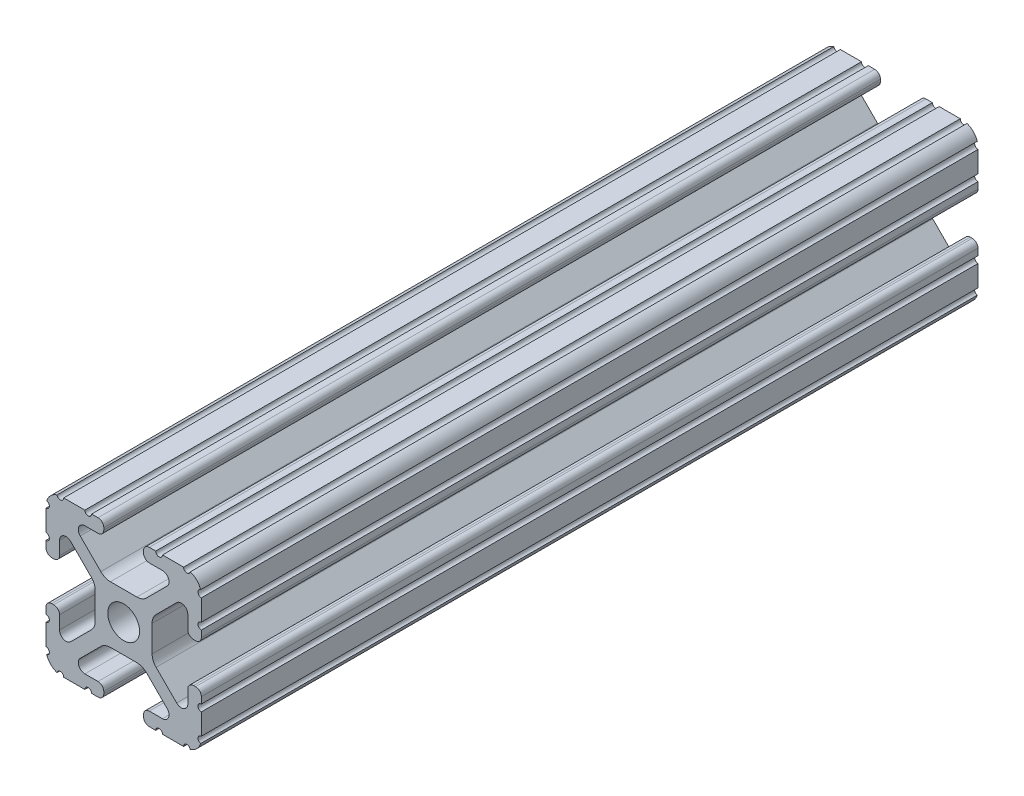
SolidWorks part; units mm, degrees
material "6061-T6 (SS)"
ref_plane "Front Plane" through (0, 0, 0) normal (0, 0, 1) x (1, 0, 0)
ref_plane "Top Plane" through (0, 0, 0) normal (0, 1, 0) x (1, 0, 0)
ref_plane "Right Plane" through (0, 0, 0) normal (1, 0, 0) x (0, 0, -1)
sketch "Sketch2" plane through (0, 0, 0) normal (0, 0, 1) x (1, 0, 0)
  line L0 (0, 12.7) -> (0, -12.7) construction
  line L1 (-12.7, 0) -> (12.7, 0) construction
  line L2 (3.2512, -12.7) -> (12.7, -12.7)
  line L3 (12.7, -12.7) -> (12.7, -3.2512)
  line L4 (3.2512, -12.7) -> (3.2512, -10.4902)
  line L5 (3.2512, -10.4902) -> (8.9276, -10.4902)
  line L6 (8.9276, -10.4902) -> (3.0856, -4.6482)
  line L7 (0, 0) -> (12.7, -12.7) construction
  line L8 (12.7, -3.2512) -> (10.4902, -3.2512)
  line L9 (10.4902, -3.2512) -> (10.4902, -8.9276)
  line L10 (10.4902, -8.9276) -> (4.6482, -3.0856)
  circle A0 centre (0, 0) radius 2.6035
  arc A1 (6.3485, -10.4902) -> (7.1039, -8.6665) centre (6.3485, -9.4219) ccw construction
  point P8 (0, -4.6482)
  dimension "Center Hole Diameter" = 5.207
  dimension "Rail Height" = 25.4
  dimension "Rail Width" = 25.4
  dimension "T-Slot Width" = 6.5024
  dimension "Slot Inner Width" = 14.8336
  dimension "Thickness" = 2.2098
  dimension "Slot Depth" = 5.842
  dimension "D1" = 2.2098
sketch "Sketch3" plane through (0, 0, 0) normal (1, 0, 0) x (0, 0, -1)
  line L0 (-152.4, -12.7) -> (152.4, -12.7) construction
  line L1 (-127, 0) -> (127, 0) construction
  dimension "D1" = 25.4
  dimension "Length" = 304.8
sketch "Sketch4" plane through (0, 0, 0) normal (0, 0, 1) x (1, 0, 0)
  line L0 (4.1904, -12.7) -> (10.1173, -12.7)
  line L1 (3.2512, -12.7) -> (12.7, -12.7) construction
  line L2 (3.2512, -12.7) -> (3.2512, -10.4902) construction
  line L3 (3.2512, -10.4902) -> (8.9276, -10.4902) construction
  line L4 (3.2512, -11.4294) -> (3.2512, -11.7608)
  line L5 (4.1904, -10.4902) -> (6.3485, -10.4902)
  line L6 (0, -4.6482) -> (2.164, -4.6482)
  line L7 (8.9276, -10.4902) -> (3.0856, -4.6482) construction
  line L8 (3.7373, -5.2999) -> (7.1039, -8.6665)
  line L9 (12.7, -12.7) -> (12.7, -3.2512) construction
  line L10 (10.4902, -8.9276) -> (4.6482, -3.0856) construction
  line L11 (10.4902, -3.2512) -> (10.4902, -8.9276) construction
  line L12 (10.4902, -6.3485) -> (10.4902, -4.1904)
  line L13 (12.7, -3.2512) -> (10.4902, -3.2512) construction
  line L14 (11.4294, -3.2512) -> (11.7608, -3.2512)
  line L15 (12.7, -4.1904) -> (12.7, -10.1173)
  line L16 (8.6665, -7.1039) -> (5.2999, -3.7373)
  line L17 (4.6482, 0) -> (4.6482, -2.164)
  line L18 (-12.7, 0) -> (12.7, 0) construction
  line L19 (0, -4.6482) -> (0, -2.6035)
  line L20 (0, 12.7) -> (0, -12.7) construction
  line L21 (4.6482, 0) -> (2.6035, 0)
  arc A0 (3.2512, -11.7608) -> (4.1904, -12.7) centre (4.1904, -11.7608) ccw
  arc A2 (3.2512, -11.4294) -> (4.1904, -10.4902) centre (4.1904, -11.4294) cw
  arc A3 (6.3485, -10.4902) -> (7.1039, -8.6665) centre (6.3485, -9.4219) ccw
  arc A4 (2.164, -4.6482) -> (3.7373, -5.2999) centre (2.164, -6.8732) cw
  arc A5 (10.1173, -12.7) -> (12.7, -10.1173) centre (10.1173, -10.1173) ccw
  arc A6 (8.6665, -7.1039) -> (10.4902, -6.3485) centre (9.4219, -6.3485) ccw
  arc A7 (10.4902, -4.1904) -> (11.4294, -3.2512) centre (11.4294, -4.1904) cw
  arc A8 (11.7608, -3.2512) -> (12.7, -4.1904) centre (11.7608, -4.1904) cw
  arc A9 (5.2999, -3.7373) -> (4.6482, -2.164) centre (6.8732, -2.164) cw
  circle A10 centre (0, 0) radius 2.6035 construction
  arc A11 (0, -2.6035) -> (2.6035, 0) centre (0, 0) ccw
  dimension "D1" = 2.5827
  dimension "D2" = 2.225
  dimension "D3" = 0.9392
extrude "Boss-Extrude1" add sketch "Sketch4" along normal mid plane 127
sketch "Sketch5" plane through (0, 0, 0) normal (0, 0, 1) x (1, 0, 0)
  line L0 (3.2512, -12.7) -> (12.7, -12.7) construction
  line L1 (4.1904, -10.4902) -> (6.3485, -10.4902) construction
  line L3 (0, 0) -> (12.7, -12.7) construction
  line L4 (6.3485, -10.4902) -> (6.3485, -12.7) construction
  line L5 (8.9276, -10.4902) -> (3.0856, -4.6482) construction
  circle A0 centre (10.3562, -12.7) radius 0.5524
  circle A1 centre (5.796, -12.7) radius 0.5524
  circle A2 centre (12.7, -10.3562) radius 0.5524
  circle A3 centre (12.7, -5.796) radius 0.5524
  point P10 (5.2694, -10.4902)
  point P12 (9.4219, -6.3485)
  dimension "D1" = 1.1049
extrude "Cut-Extrude1" cut sketch "Sketch5" against normal through all both and the other way through all
mirror "Mirror1" about plane through (0, 0, 0) normal (1, 0, 0) of bodies 137 134
mirror "Mirror2" about plane through (0, 0, 0) normal (0, 1, 0) of bodies 135
equation "\"D1@Boss-Extrude1\"=5"
equation "\"D1@Sketch2\"= \"Thickness@Sketch2\""
equation "\"D2@Sketch4\"=\"Slot Inner Width@Sketch2\"*0.15"
equation "\"D1@Sketch4\"=\"D3@Sketch4\"*2.75"
equation "\"D3@Sketch4\"=\"Thickness@Sketch2\"*0.425"
equation "\"D1@Sketch5\"=\"Thickness@Sketch2\"*0.5"
